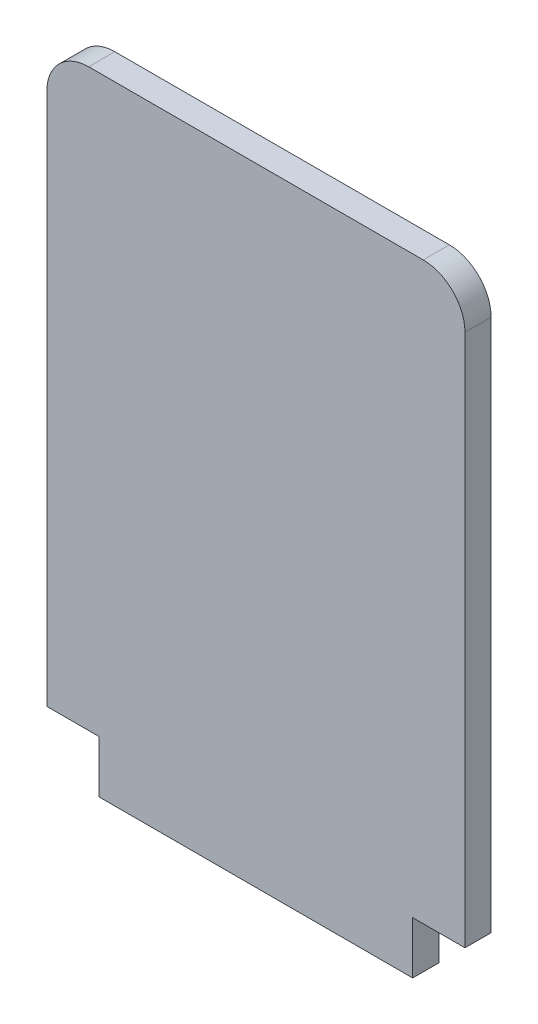
SolidWorks part; units mm, degrees
ref_plane "Front Plane" through (0, 0, 0) normal (0, 0, 1) x (1, 0, 0)
ref_plane "Top Plane" through (0, 0, 0) normal (0, 1, 0) x (1, 0, 0)
ref_plane "Right Plane" through (0, 0, 0) normal (1, 0, 0) x (0, 0, -1)
sketch "Sketch1" plane through (0, 0, 0) normal (0, 0, 1) x (1, 0, 0)
  line L0 (88.9, 0) -> (101.6, 0)
  line L1 (0, 0) -> (12.7, 0)
  line L2 (0, 0) -> (0, 139.7)
  line L3 (0, 139.7) -> (101.6, 139.7)
  line L4 (101.6, 0) -> (101.6, 139.7)
  line L6 (12.7, 0) -> (12.7, -12.7)
  line L7 (12.7, -12.7) -> (88.9, -12.7)
  line L8 (88.9, 0) -> (88.9, -12.7)
  dimension "D1" = 139.7
  dimension "D2" = 101.6
  dimension "D3" = 12.7
  dimension "D4" = 76.2
  dimension "D5" = 12.7
extrude "Boss-Extrude1" add sketch "Sketch1" along normal blind 6.35
fillet "Fillet1" radius 10.16 2 edges at (101.6, 139.7, 3.175) (0, 139.7, 3.175)
